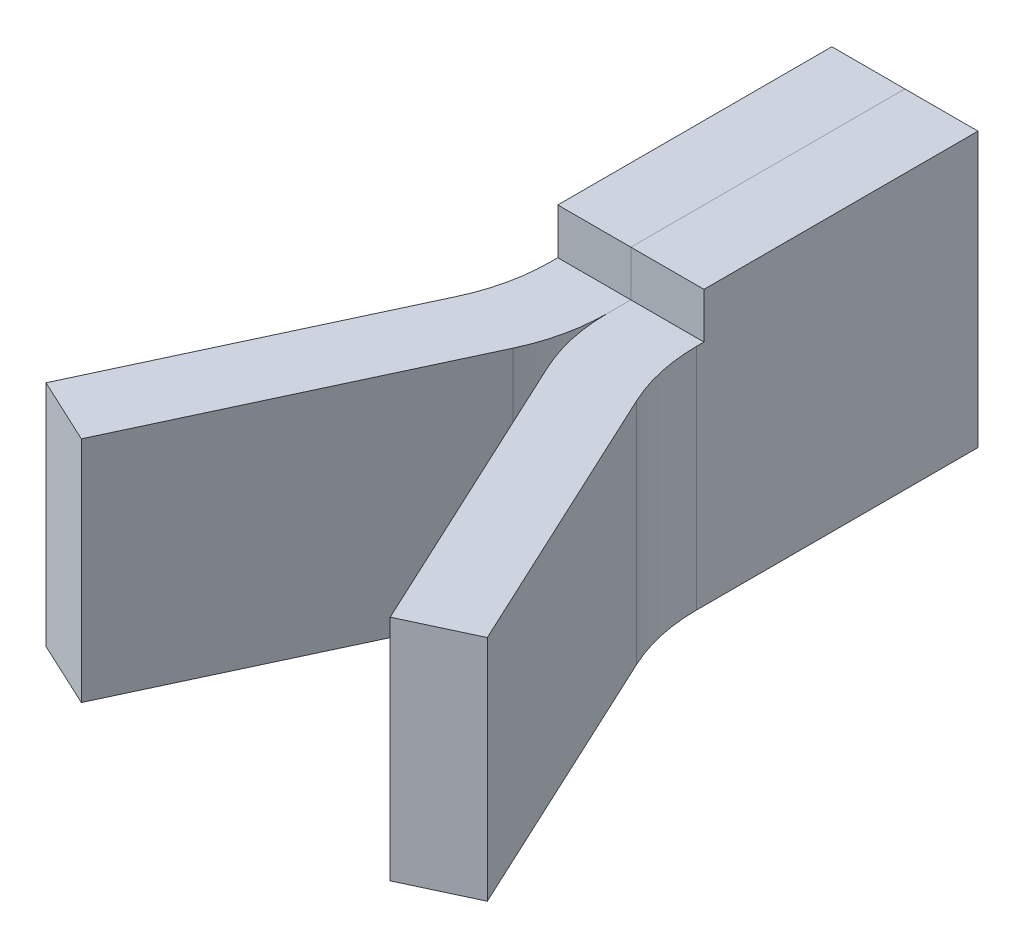
SolidWorks part; units mm, degrees
ref_plane "前视基准面" through (0, 0, 0) normal (0, 0, 1) x (1, 0, 0)
ref_plane "上视基准面" through (0, 0, 0) normal (0, 1, 0) x (1, 0, 0)
ref_plane "右视基准面" through (0, 0, 0) normal (1, 0, 0) x (0, 0, -1)
sketch "Sketch1" plane through (0, 0, 0) normal (0, 1, 0) x (1, 0, 0)
  line L0 (0, 0) -> (0, 37)
  line L1 (0, 37) -> (8, 37)
  line L2 (8, 37) -> (8, 1.7736)
  line L3 (8, 1.7736) -> (24.1552, -32.8714)
  line L4 (24.1552, -32.8714) -> (16.9047, -36.2523)
  line L5 (16.9047, -36.2523) -> (0, 0)
  dimension "D1" = 8
  dimension "D2" = 37
  dimension "D3" = 8
  dimension "D4" = 40
  dimension "D5" = 155
extrude "Boss-Extrude1" add sketch "Sketch1" along normal blind 25
sketch "Sketch2" plane through (0, 25, 0) normal (0, 1, 0) x (1, 0, 0)
  line L0 (8, 37) -> (0, 37)
  line L1 (8, 37) -> (8, 7)
  line L2 (0, 37) -> (0, 7)
  line L3 (8, 7) -> (0, 7)
  line L4 (8, 37) -> (0, 37) construction
  dimension "D1" = 30
extrude "Boss-Extrude2" add sketch "Sketch2" along normal blind 5
fillet "Fillet1" radius 20 2 edges at (8, 12.5, -1.7736) (0, 12.5, 0)
mirror "Mirror1" about plane through (0, 0, 0) normal (1, 0, 0) of bodies 107
